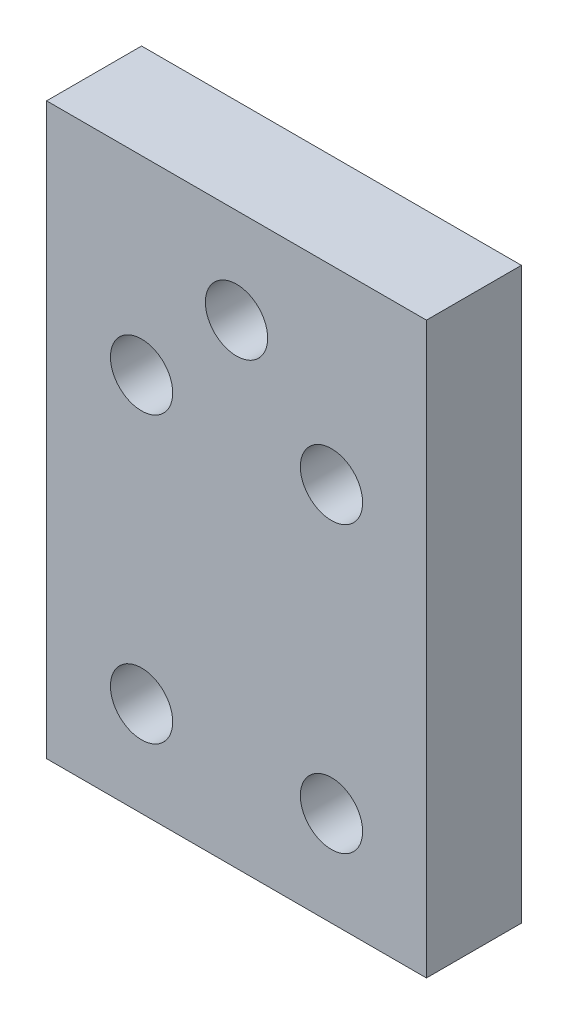
SolidWorks part; units mm, degrees
ref_plane "Front Plane" through (0, 0, 0) normal (0, 0, 1) x (1, 0, 0)
ref_plane "Top Plane" through (0, 0, 0) normal (0, 1, 0) x (1, 0, 0)
ref_plane "Right Plane" through (0, 0, 0) normal (1, 0, 0) x (0, 0, -1)
sketch "Sketch1" plane through (0, 0, 0) normal (0, 0, 1) x (1, 0, 0)
  line L0 (0, 12.7) -> (0, 50.8)
  line L1 (0, 50.8) -> (25.4, 50.8)
  line L2 (25.4, 50.8) -> (25.4, 12.7)
  line L3 (6.35, 31.75) -> (6.35, 38.1) construction
  line L4 (0, 31.75) -> (25.4, 31.75) construction
  line L5 (19.05, 31.75) -> (19.05, 38.1) construction
  line L6 (25.4, 19.05) -> (19.05, 19.05) construction
  line L8 (12.7, 50.8) -> (12.7, 12.7) construction
  line L9 (0, 19.05) -> (6.35, 19.05) construction
  line L10 (25.4, 12.7) -> (0, 12.7)
  circle A0 centre (6.35, 19.05) radius 2.0828
  circle A1 centre (6.35, 38.1) radius 2.0828
  circle A2 centre (12.7, 44.45) radius 2.0828
  circle A3 centre (19.05, 19.05) radius 2.0828
  circle A4 centre (19.05, 38.1) radius 2.0828
  dimension "D2" = 12.7
  dimension "D1" = 19.05
  dimension "D4" = 12.7
extrude "Boss-Extrude1" add sketch "Sketch1" along normal blind 6.35
sketch "Sketch2" plane through (0, 12.7, 0) normal (0, -1, 0) x (1, 0, 0)
  line L0 (12.7, 0) -> (12.7, 6.35) construction
  line L1 (0, 0) -> (25.4, 0) construction
  line L2 (0, 6.35) -> (25.4, 6.35) construction
  line L3 (20.066, 3.175) -> (5.334, 3.175) construction
  circle A0 centre (5.334, 3.175) radius 0.635
  circle A1 centre (20.066, 3.175) radius 0.635
  point P10 (12.7, 3.175)
extrude "Cut-Extrude1" cut sketch "Sketch2" against normal blind 3.556
